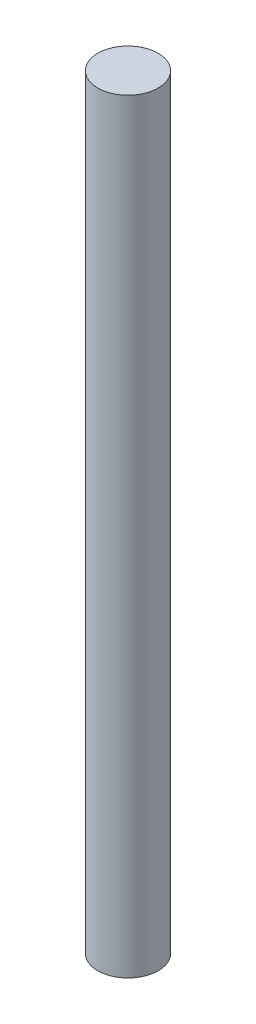
SolidWorks part; units mm, degrees
ref_plane "前视基准面" through (0, 0, 0) normal (0, 0, 1) x (1, 0, 0)
ref_plane "上视基准面" through (0, 0, 0) normal (0, 1, 0) x (1, 0, 0)
ref_plane "右视基准面" through (0, 0, 0) normal (1, 0, 0) x (0, 0, -1)
other "Configuration Table"
sketch "草图1" plane through (0, 0, 0) normal (0, 1, 0) x (1, 0, 0)
  circle A0 centre (0, 0) radius 1.5
  dimension "D1" = 3
extrude "凸台-拉伸1" add sketch "草图1" along normal blind 38
